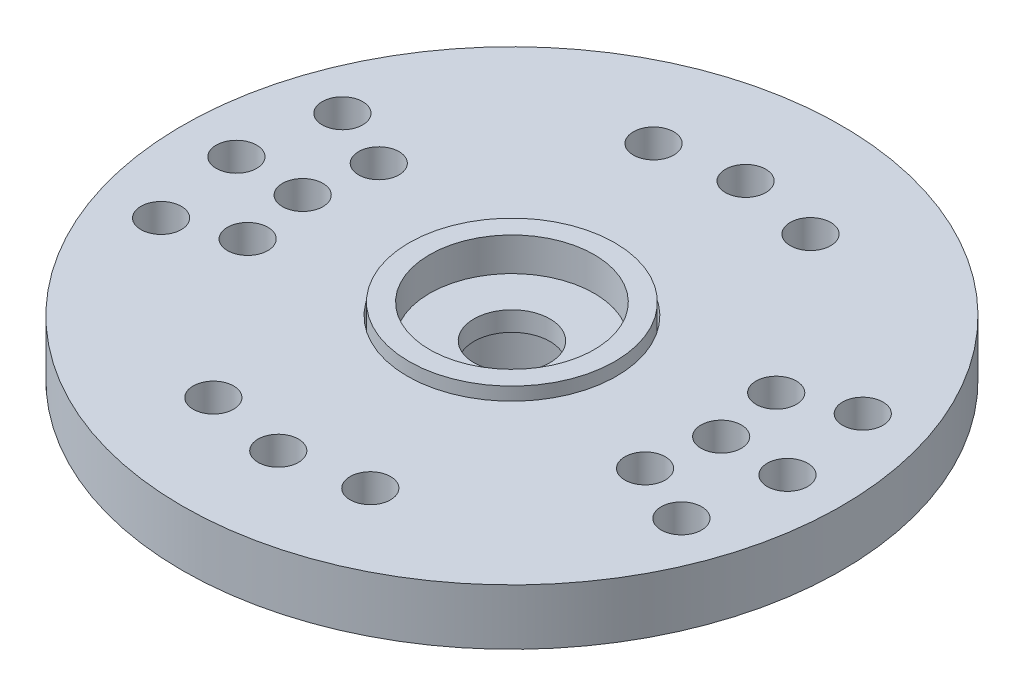
SolidWorks part; units mm, degrees
material "Nylon 6/10"
ref_plane "Front" through (0, 0, 0) normal (0, 0, 1) x (1, 0, 0)
ref_plane "Top" through (0, 0, 0) normal (0, 1, 0) x (1, 0, 0)
ref_plane "Right" through (0, 0, 0) normal (1, 0, 0) x (0, 0, -1)
sketch "Sketch1" plane through (0, 0, 0) normal (0, 1, 0) x (1, 0, 0)
  line L0 (0, 25.4919) -> (0, -27.5589) construction
  circle A0 centre (0, 8.509) radius 0.7366
  circle A1 centre (0, -8.509) radius 0.7366
  circle A2 centre (7.62, 0) radius 0.7366
  circle A3 centre (-7.62, 0) radius 0.7366
  circle A4 centre (2.8575, -8.0148) radius 0.7366
  circle A5 centre (2.8575, 8.0148) radius 0.7366
  circle A6 centre (-2.8575, -8.0148) radius 0.7366
  circle A7 centre (-2.8575, 8.0148) radius 0.7366
  circle A8 centre (0, 0) radius 12.0015
  circle A9 centre (0, 0) radius 8.509 construction
  circle A10 centre (0, 0) radius 7.62 construction
  circle A11 centre (0, 0) radius 10.033 construction
  circle A12 centre (7.2363, 2.3876) radius 0.7366
  circle A13 centre (7.2363, -2.3876) radius 0.7366
  circle A14 centre (9.4741, 3.302) radius 0.7366
  circle A15 centre (9.4741, -3.302) radius 0.7366
  circle A16 centre (-7.2363, -2.3876) radius 0.7366
  circle A17 centre (-9.4741, -3.302) radius 0.7366
  circle A18 centre (-9.4741, 3.302) radius 0.7366
  circle A19 centre (-7.2363, 2.3876) radius 0.7366
  circle A20 centre (10.033, 0) radius 0.7366
  circle A21 centre (-10.033, 0) radius 0.7366
  circle A22 centre (0, 0) radius 3.81
  dimension "D3" = 1.4732
  dimension "D6" = 24.003
  dimension "D1" = 8.509
  dimension "D2" = 7.62
  dimension "D4" = 5.715
  dimension "D7" = 20.066
  dimension "D9" = 7.62
  dimension "D5" = 6.604
  dimension "D8" = 4.7752
extrude "Boss-Extrude1" add sketch "Sketch1" along normal blind 2.032
sketch "Sketch3" plane through (0, 0, 0) normal (0, 0, 1) x (1, 0, 0)
  line L0 (0, 2.4638) -> (0, -8.8147) construction
  line L2 (1.3843, 0.5334) -> (2.794, 0.5334)
  line L3 (2.794, 0.5334) -> (2.794, -2.5146)
  line L4 (2.794, -2.5146) -> (4.445, -2.5146)
  line L5 (4.445, -2.5146) -> (4.445, 0)
  line L6 (-12.0015, 0) -> (12.0015, 0) construction
  line L7 (3.7465, 2.4638) -> (3.7465, 0)
  line L8 (2.9972, 2.4638) -> (3.7465, 2.4638)
  line L10 (3.7465, 0) -> (4.445, 0)
  line L11 (2.9972, 2.4638) -> (2.9972, 1.2446)
  line L12 (2.9972, 1.2446) -> (1.3843, 1.2446)
  line L13 (1.3843, 1.2446) -> (1.3843, 0.5334)
  dimension "D1" = 5.588
  dimension "D2" = 8.89
  dimension "D3" = 2.5146
  dimension "D4" = 3.048
  dimension "D5" = 4.9784
  dimension "D6" = 7.493
  dimension "D7" = 5.9944
  dimension "D8" = 1.2192
  dimension "D9" = 2.7686
revolve "hub" add sketch "Sketch3" angle 360 about L0
